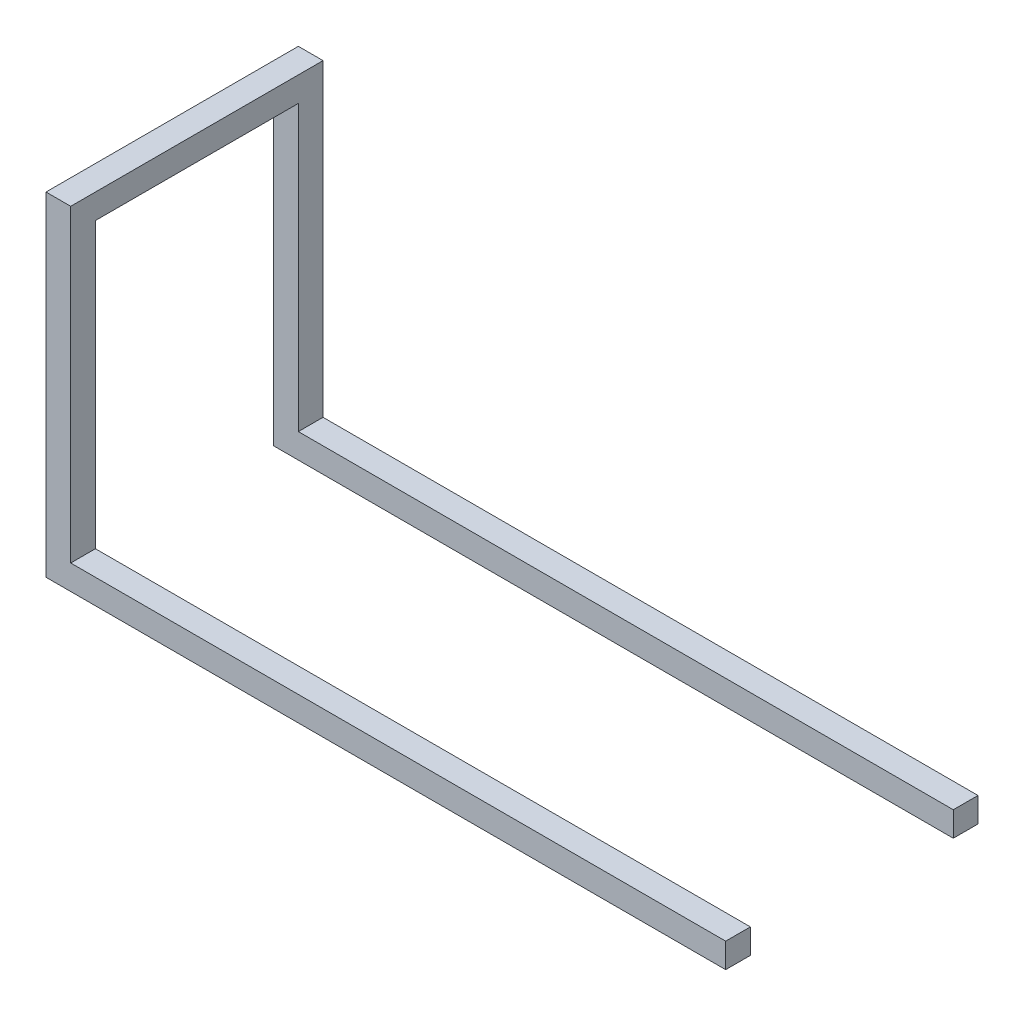
SolidWorks part; units mm, degrees
ref_plane "前视基准面" through (0, 0, 0) normal (0, 0, 1) x (1, 0, 0)
ref_plane "上视基准面" through (0, 0, 0) normal (0, 1, 0) x (1, 0, 0)
ref_plane "右视基准面" through (0, 0, 0) normal (1, 0, 0) x (0, 0, -1)
ref_plane "基准面4" through (0, 0, 164.2) normal (0, 0, 1) x (1, 0, 0)
sketch "草图2" plane through (0, 0, 164.2) normal (0, 0, 1) x (1, 0, 0)
  line L2 (-475, 0) -> (585, 0)
  line L18 (-515, 500) -> (-475, 500)
  line L19 (-475, 0) -> (-475, 460)
  line L23 (-515, 500) -> (-515, -40)
  line L24 (-515, -40) -> (585, -40)
  line L25 (585, -40) -> (585, 0)
  line L26 (-475, 460) -> (-475, 500)
  point P13 (-15, -40)
  point P19 (-250, 460)
  dimension "D2" = 1100
  dimension "D3" = 40
  dimension "D4" = 540
  dimension "D6" = 40
extrude "凸台-拉伸1" add sketch "草图2" along normal blind 40
mirror "镜向4" about plane through (0, 0, 0) normal (0, 0, 1) of bodies 101 108
sketch "草图6" plane through (0, 500, 0) normal (0, 1, 0) x (1, 0, 0)
  line L0 (-475, -204.2) -> (-475, 204.2)
  line L2 (-515, 204.2) -> (-515, -204.2)
  line L9 (-475, 204.2) -> (-515, 204.2)
  line L10 (-475, -204.2) -> (-515, -204.2)
  dimension "D1" = 40
extrude "凸台-拉伸2" add sketch "草图6" against normal blind 40
